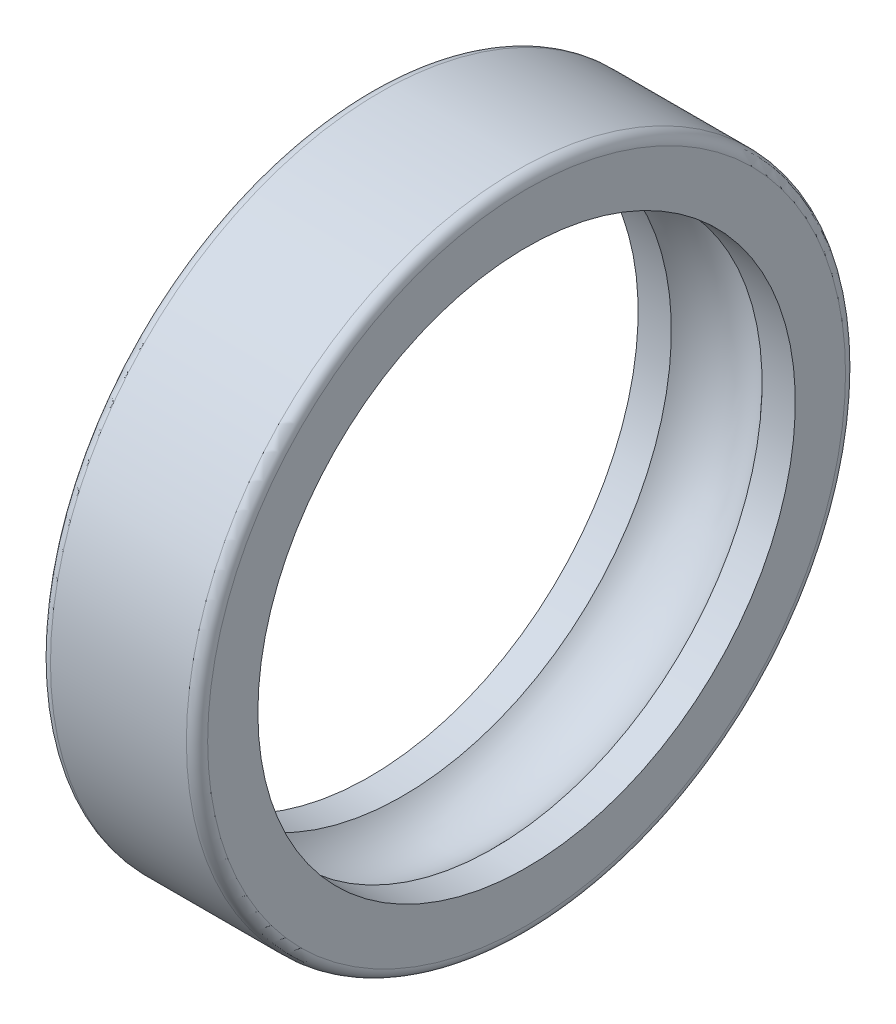
SolidWorks part; units mm, degrees
ref_plane "Front Plane" through (0, 0, 0) normal (0, 0, 1) x (1, 0, 0)
ref_plane "Top Plane" through (0, 0, 0) normal (0, 1, 0) x (1, 0, 0)
ref_plane "Right Plane" through (0, 0, 0) normal (1, 0, 0) x (0, 0, -1)
sketch "Sketch1" plane through (0, 0, 0) normal (0, 0, 1) x (1, 0, 0)
  line L0 (-8.0636, 0) -> (31.9364, 0) construction
  line L2 (15.5, 65) -> (-15.5, 65)
  line L3 (15.5, 65) -> (15.5, 53)
  line L4 (15.5, 53) -> (8.9443, 53)
  line L5 (-15.5, 65) -> (-15.5, 53)
  line L6 (15.5, 65) -> (-15.5, 53) construction
  line L7 (15.5, 53) -> (-15.5, 65) construction
  line L8 (-8.9443, 53) -> (-15.5, 53)
  arc A0 (-8.9443, 53) -> (8.9443, 53) centre (0, 45) cw
  point P3 (0, 59)
  dimension "D1" = 31
  dimension "D2" = 40
  dimension "D3" = 53
  dimension "D4" = 65
  dimension "D5" = 8
revolve "Revolve2" add sketch "Sketch1" angle 360 about L0
fillet "Fillet1" radius 2.1 2 edges at (15.5, 0, 65) (-15.5, 0, 65)
